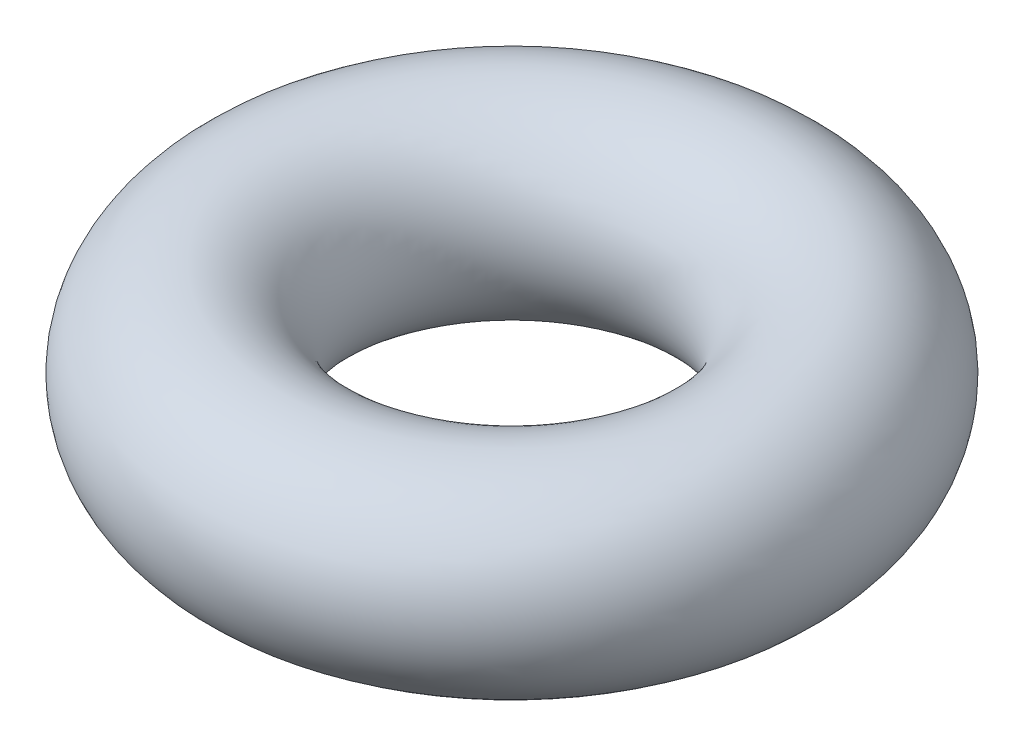
SolidWorks part; units mm, degrees
ref_plane "Спереди" through (0, 0, 0) normal (0, 0, 1) x (1, 0, 0)
ref_plane "Сверху" through (0, 0, 0) normal (0, 1, 0) x (1, 0, 0)
ref_plane "Справа" through (0, 0, 0) normal (1, 0, 0) x (0, 0, -1)
other "Configuration Table"
sketch "Эскиз1" plane through (0, 0, 0) normal (0, 0, 1) x (1, 0, 0)
  line L0 (0, 0) -> (0, 37.3741) construction
  circle A0 centre (-60, 0) radius 25
  circle A1 centre (-60, 0) radius 12.5
  dimension "D2" = 50
  dimension "D3" = 25
  dimension "D1" = 60
revolve "Повернуть1" add sketch "Эскиз1" angle 360 about L0
